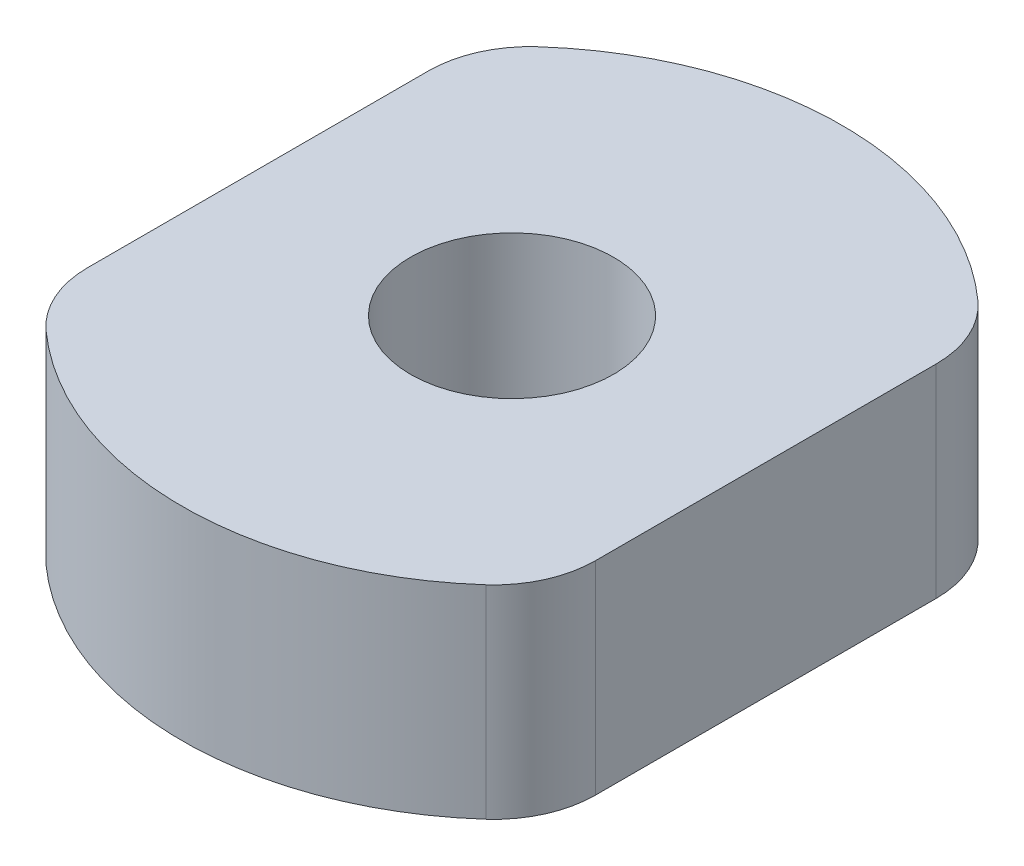
SolidWorks part; units mm, degrees
ref_plane "Front Plane" through (0, 0, 0) normal (0, 0, 1) x (1, 0, 0)
ref_plane "Top Plane" through (0, 0, 0) normal (0, 1, 0) x (1, 0, 0)
ref_plane "Right Plane" through (0, 0, 0) normal (1, 0, 0) x (0, 0, -1)
sketch "Sketch1" plane through (0, 0, 0) normal (0, 1, 0) x (1, 0, 0)
  line L0 (0, 0) -> (0, 52.2319) construction
  line L1 (-31.75, 21.2985) -> (-31.75, -21.2985)
  line L2 (31.75, 21.2985) -> (31.75, -21.2985)
  arc A0 (27.5167, 30.7646) -> (-27.5167, 30.7646) centre (0, 0) ccw
  arc A1 (-27.5167, -30.7646) -> (27.5167, -30.7646) centre (0, 0) ccw
  arc A2 (-31.75, -21.2985) -> (-27.5167, -30.7646) centre (-19.05, -21.2985) ccw
  circle A3 centre (0, 0) radius 12.7
  arc A4 (-31.75, 21.2985) -> (-27.5167, 30.7646) centre (-19.05, 21.2985) cw
  arc A5 (31.75, 21.2985) -> (27.5167, 30.7646) centre (19.05, 21.2985) ccw
  arc A6 (31.75, -21.2985) -> (27.5167, -30.7646) centre (19.05, -21.2985) cw
  point P11 (-31.75, -26.3735)
  point P14 (-31.75, 26.3735)
  point P17 (31.75, 26.3735)
  point P20 (31.75, -26.3735)
  dimension "D1" = 82.55
  dimension "D2" = 63.5
  dimension "D4" = 25.4
  dimension "D3" = 12.7
extrude "Extrude2" add sketch "Sketch1" along normal blind 25.4
